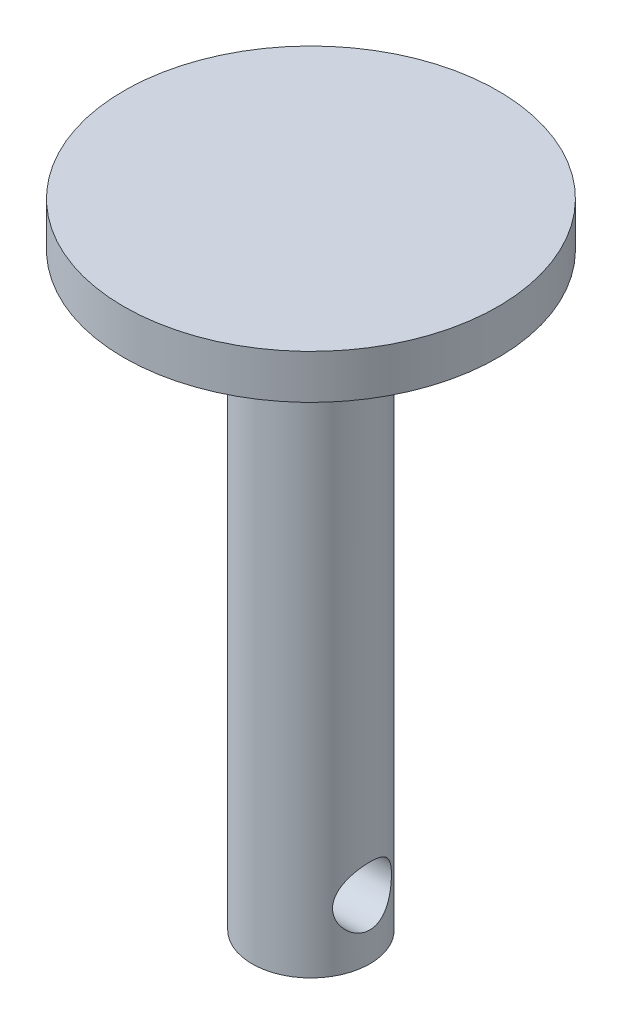
SolidWorks part; units mm, degrees
ref_plane "Alzado" through (0, 0, 0) normal (0, 0, 1) x (1, 0, 0)
ref_plane "Planta" through (0, 0, 0) normal (0, 1, 0) x (1, 0, 0)
ref_plane "Vista lateral" through (0, 0, 0) normal (1, 0, 0) x (0, 0, -1)
sketch "Croquis1" plane through (0, 0, 0) normal (0, 1, 0) x (1, 0, 0)
  circle A0 centre (0, 0) radius 12.7
  dimension "D1" = 25.4
extrude "Saliente-Extruir1" add sketch "Croquis1" along normal blind 3
sketch "Croquis2" plane through (0, 0, 0) normal (0, -1, 0) x (1, 0, 0)
  circle A0 centre (0, 0) radius 4
  dimension "D1" = 8
extrude "Saliente-Extruir2" add sketch "Croquis2" along normal blind 40
sketch "Croquis3" plane through (0, 0, 0) normal (0, -1, 0) x (-1, 0, 0)
  line L0 (1.1045, 3.8445) -> (3.5068, 12.2063)
  circle A0 centre (0, 0) radius 4 construction
  circle A1 centre (0, 0) radius 12.7 construction
ref_plane "Plano1" through (4, 0, 0) normal (1, 0, 0) x (0, 0, -1)
sketch "Croquis4" plane through (4, 0, 0) normal (1, 0, 0) x (0, 0, -1)
  line L0 (-4, -40) -> (4, -40) construction
  circle A0 centre (0, -36) radius 2
  point P2 (0, -10.2801)
  dimension "D1" = 4
  dimension "D2" = 4
extrude "Cortar-Extruir1" cut sketch "Croquis4" against normal blind 10
